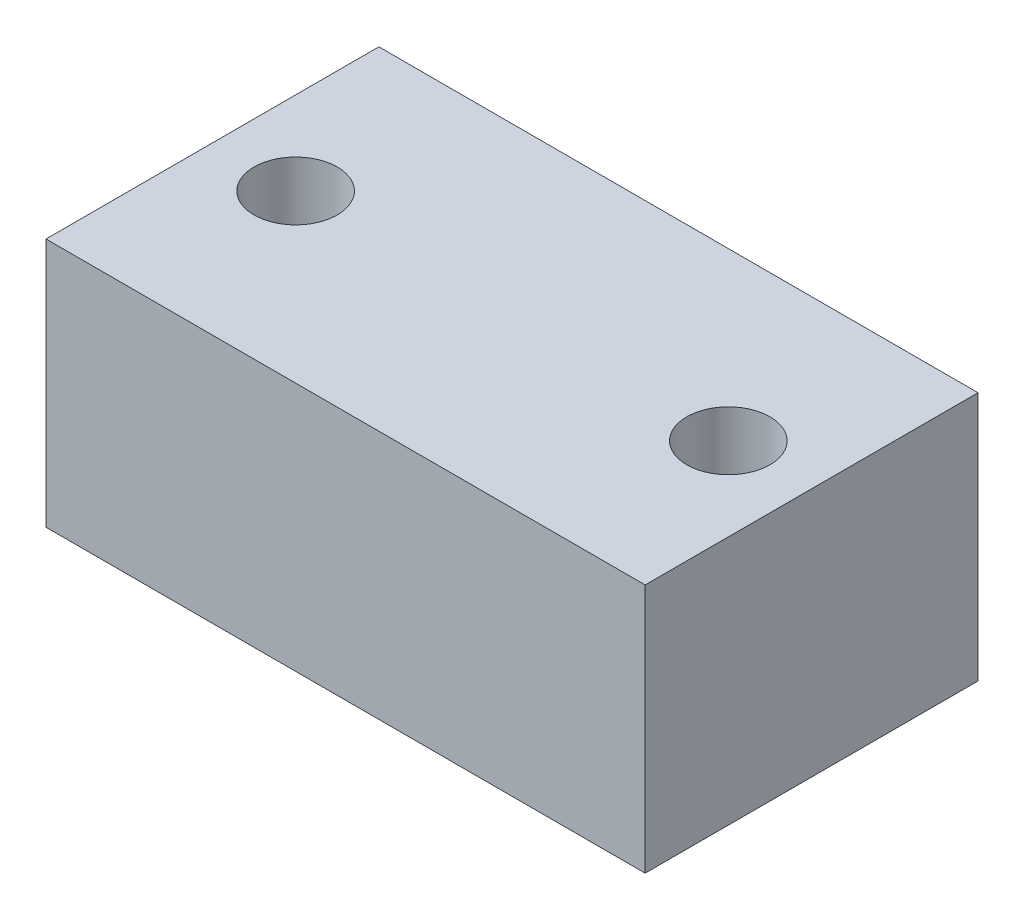
SolidWorks part; units mm, degrees
ref_plane "Front Plane" through (0, 0, 0) normal (0, 0, 1) x (1, 0, 0)
ref_plane "Top Plane" through (0, 0, 0) normal (0, 1, 0) x (1, 0, 0)
ref_plane "Right Plane" through (0, 0, 0) normal (1, 0, 0) x (0, 0, -1)
sketch "Sketch1" plane through (0, 0, 0) normal (0, 1, 0) x (1, 0, 0)
  line L1 (-18, 10) -> (18, 10)
  line L2 (-18, 10) -> (-18, -10)
  line L3 (-18, -10) -> (18, -10)
  line L4 (18, 10) -> (18, -10)
  line L5 (-18, 10) -> (18, -10) construction
  line L6 (-18, -10) -> (18, 10) construction
  point P0 (0, 0)
  dimension "D1" = 36
  dimension "D2" = 20
extrude "Boss-Extrude1" add sketch "Sketch1" along normal blind 15
sketch "Sketch4" plane through (0, 15, 0) normal (0, 1, 0) x (1, 0, 0)
  line L0 (0, 10) -> (0, -10) construction
  line L1 (18, 10) -> (-18, 10) construction
  line L2 (-18, -10) -> (18, -10) construction
  circle A0 centre (13, 0) radius 2.5
  circle A1 centre (-13, 0) radius 2.5
  dimension "D1" = 5
  dimension "D2" = 13
extrude "Cut-Extrude1" cut sketch "Sketch4" against normal blind 10
